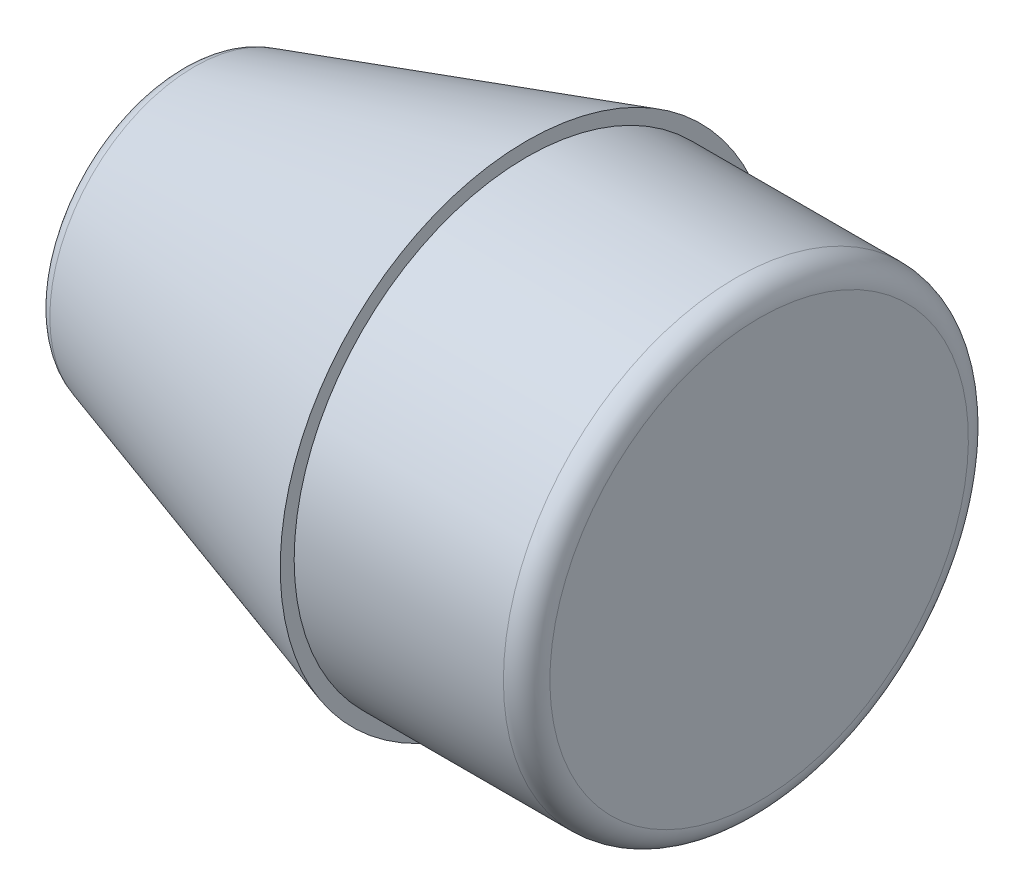
SolidWorks part; units mm, degrees
ref_plane "Plano frontal" through (0, 0, 0) normal (0, 0, 1) x (1, 0, 0)
ref_plane "Plano superior" through (0, 0, 0) normal (0, 1, 0) x (1, 0, 0)
ref_plane "Plano direito" through (0, 0, 0) normal (1, 0, 0) x (0, 0, -1)
sketch "Esboço1" plane through (0, 0, 0) normal (0, 0, 1) x (1, 0, 0)
  line L0 (0, 0) -> (0, 3)
  line L1 (0, 3) -> (7.5, 5.3)
  line L2 (7.5, 5.3) -> (7.5, 5)
  line L3 (7.5, 5) -> (12.5, 5)
  line L4 (12.5, 5) -> (12.5, 0)
  line L5 (12.5, 0) -> (0, 0)
  dimension "D1" = 5
  dimension "D2" = 5
  dimension "D3" = 3
  dimension "D4" = 12.5
  dimension "D5" = 0.3
revolve "Revolução1" add sketch "Esboço1" angle 360 about L5
fillet "Filete1" radius 0.5 1 edges at (12.5, 5, 0)
fillet "Filete2" radius 0.5 1 edges at (0, 3, 0)
